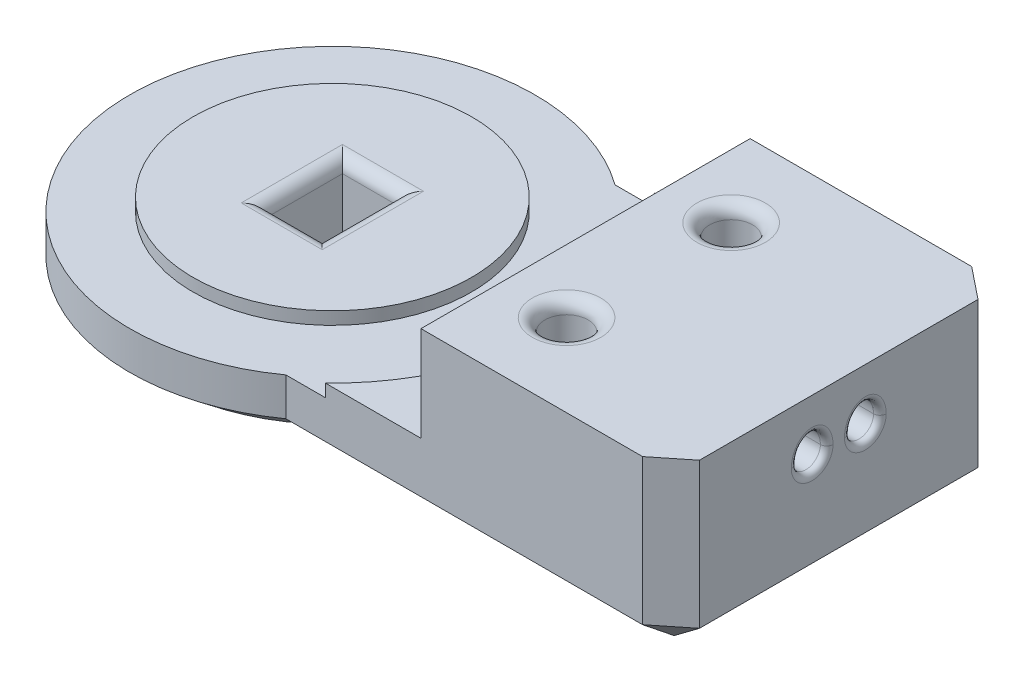
SolidWorks part; units mm, degrees
ref_plane "Front Plane" through (0, 0, 0) normal (0, 0, 1) x (1, 0, 0)
ref_plane "Top Plane" through (0, 0, 0) normal (0, 1, 0) x (1, 0, 0)
ref_plane "Right Plane" through (0, 0, 0) normal (1, 0, 0) x (0, 0, -1)
sketch "Sketch1" plane through (0, 0, 0) normal (0, 1, 0) x (1, 0, 0)
  line L0 (-1.1, 1.0198) -> (-1.1, -1.0198)
  line L1 (1.1, 1.0198) -> (1.1, -1.0198)
  line L2 (-998.0463, -6.5) -> (49001.9537, -6.5) construction
  line L3 (-998.5569, 6.5) -> (49001.4431, 6.5) construction
  line L4 (15, -1002.9744) -> (15, 48997.0256) construction
  line L5 (4.6637, 6.5) -> (15, 6.5)
  line L6 (15, 6.5) -> (15, -6.5)
  line L7 (15, -6.5) -> (4.6637, -6.5)
  line L8 (0.887, 1.2096) -> (1.1, 1.5) construction
  line L9 (-1.1, 1.5) -> (1.1, 1.5)
  line L10 (-1.1, 1.5) -> (-1.1, -1.5)
  line L11 (-1.1, -1.5) -> (1.1, -1.5)
  line L12 (1.1, 1.5) -> (1.1, -1.5)
  line L13 (-0.887, 1.2096) -> (1.1, -1.5) construction
  line L14 (-1.1, -1.5) -> (0.887, 1.2096) construction
  line L15 (-1.1, 1.5) -> (-0.887, 1.2096) construction
  arc A0 (-1.1, -1.0198) -> (-0.887, -1.2096) centre (0, 0) ccw construction
  arc A1 (-1.1, 1.0198) -> (-1.1, -1.0198) centre (0, 0) ccw construction
  arc A2 (1.1, -1.0198) -> (1.1, 1.0198) centre (0, 0) ccw construction
  arc A3 (-0.887, 1.2096) -> (-1.1, 1.0198) centre (0, 0) ccw construction
  arc A4 (4.6637, 6.5) -> (4.6637, -6.5) centre (0, 0) ccw
  arc A5 (4.6637, -6.5) -> (4.6637, 6.5) centre (0, 0) ccw construction
  arc A6 (-0.887, -1.2096) -> (0, -1.5) centre (0, 0) ccw construction
  arc A7 (0.887, -1.2096) -> (1.1, -1.0198) centre (0, 0) ccw construction
  arc A8 (0, -1.5) -> (0.887, -1.2096) centre (0, 0) ccw construction
  arc A9 (1.1, 1.0198) -> (0.887, 1.2096) centre (0, 0) ccw construction
  arc A10 (0.887, 1.2096) -> (0, 1.5) centre (0, 0) ccw construction
  arc A11 (0, 1.5) -> (-0.887, 1.2096) centre (0, 0) ccw construction
  dimension "D1" = 3
  dimension "D4" = 16
  dimension "D2" = 1.1
  dimension "D3" = 1.1
  dimension "D5" = 6.5
  dimension "D6" = 6.5
  dimension "D7" = 15
extrude "Boss-Extrude1" add sketch "Sketch1" against normal blind 3 contours L5 A4 L7 L6 L9 L12 L1 L11 L10 L0
sketch "Sketch2" plane through (0, 0, 0) normal (0, 1, 0) x (1, 0, 0)
  circle A0 centre (0, 0) radius 9
  circle A1 centre (0, 0) radius 5.5
  dimension "D1" = 18
  dimension "D2" = 3.5
extrude "Cut-Extrude1" cut sketch "Sketch2" against normal blind 0.5
sketch "Sketch3" plane through (0, 0, 0) normal (0, 1, 0) x (1, 0, 0)
  line L1 (15, 6.5) -> (10, 6.5)
  line L2 (15, 6.5) -> (15, -6.5)
  line L3 (15, -6.5) -> (10, -6.5)
  line L4 (10, 6.5) -> (10, -6.5)
  line L5 (15, -6.5) -> (6.2249, -6.5) construction
  dimension "D1" = 10
extrude "Boss-Extrude2" add sketch "Sketch3" along normal blind 3.75
sketch "Sketch4" plane through (0, -3, 0) normal (0, -1, 0) x (1, 0, 0)
  line L0 (10, 6.5) -> (10, -6.5) construction
  line L3 (12.5, 6.5) -> (12.5, -6.5) construction
  line L5 (10, 6.5) -> (15, 0) construction
  line L6 (15, 0) -> (10, -6.5) construction
  line L7 (15, -6.5) -> (15, 6.5) construction
  line L8 (15, 6.5) -> (4.6637, 6.5) construction
  line L9 (4.6637, -6.5) -> (15, -6.5) construction
  circle A0 centre (12.5, 3.25) radius 0.85
  circle A1 centre (12.5, -3.25) radius 0.85
  dimension "D3" = 1.7
  dimension "D4" = 1.7
  dimension "D1" = 2.5
  dimension "D2" = 2.5
extrude "Cut-Extrude2" cut sketch "Sketch4" against normal through all both and the other way through all
sketch "Sketch5" plane through (0, -3, 0) normal (0, -1, 0) x (1, 0, 0)
  line L0 (15, -6.5) -> (20, -6.5)
  line L1 (15, 6.5) -> (20, 6.5)
  line L2 (20, 6.5) -> (20, -6.5)
  line L3 (15, 6.5) -> (15, -6.5)
  dimension "D1" = 10
extrude "Boss-Extrude3" add sketch "Sketch5" against normal up to vertex (6.75 mm away)
chamfer "Chamfer1" distance 1 distance2 1.25 6 edges at (20, -3, 0) (20, 0.375, -6.5) (20, 0.375, 6.5) (-8, -3, 0) (12.3318, -3, -6.5) (12.3318, -3, 6.5)
fillet "Fillet1" radius 0.5 12 edges at (13.35, 3.75, -3.25) (13.35, 3.75, 3.25) (11.65, -3, -3.25) (11.65, -3, 3.25) (0, -3, -1.5) (-1.1, -3, 0) (0, -3, 1.5) (1.1, -3, 0) (-1.1, 0, 0) (0, 0, -1.5) (0, 0, 1.5) (1.1, 0, 0)
sketch "Sketch6" plane through (10, 0, 0) normal (-1, 0, 0) x (0, 0, 1)
  line L0 (6.5, 1.65) -> (-6.5, 1.65) construction
  line L4 (-6.5, 0) -> (6.5, 0) construction
  arc A0 (0.475, 1.65) -> (1.625, 1.65) centre (1.05, 1.65) ccw
  arc A1 (-1.625, 1.65) -> (-0.475, 1.65) centre (-1.05, 1.65) ccw
  arc A2 (1.625, 1.65) -> (0.475, 1.65) centre (1.05, 1.65) ccw construction
  arc A3 (-0.475, 1.65) -> (-1.625, 1.65) centre (-1.05, 1.65) ccw construction
  ellipse E0 centre (-1.05, 1.65) end of major axis (-1.05, 2.4) minor radius 0.575 (-0.475, 1.65) -> (-1.625, 1.65) ccw
  ellipse E1 centre (1.05, 1.65) end of major axis (1.05, 2.4) minor radius 0.575 (1.625, 1.65) -> (0.475, 1.65) ccw
  ellipse E2 centre (-1.05, 1.65) end of major axis (-1.05, 2.4) minor radius 0.575 (-1.625, 1.65) -> (-0.475, 1.65) ccw construction
  ellipse E3 centre (1.05, 1.65) end of major axis (1.05, 2.4) minor radius 0.575 (0.475, 1.65) -> (1.625, 1.65) ccw construction
  point P1 (-1.05, 2.4)
  dimension "D1" = 1.15
  dimension "D2" = 1.15
  dimension "D3" = 2.1
  dimension "D4" = 1.05
  dimension "D5" = 1.65
  dimension "D6" = 0.75
  dimension "D7" = 0.75
extrude "Cut-Extrude3" cut sketch "Sketch6" against normal through all
fillet "Fillet2" radius 0.25 8 edges at (10, 1.075, -1.05) (20, 1.075, -1.05) (10, 1.075, 1.05) (20, 1.075, 1.05) (20, 2.4, -1.05) (10, 2.4, -1.05) (20, 2.4, 1.05) (10, 2.4, 1.05)
